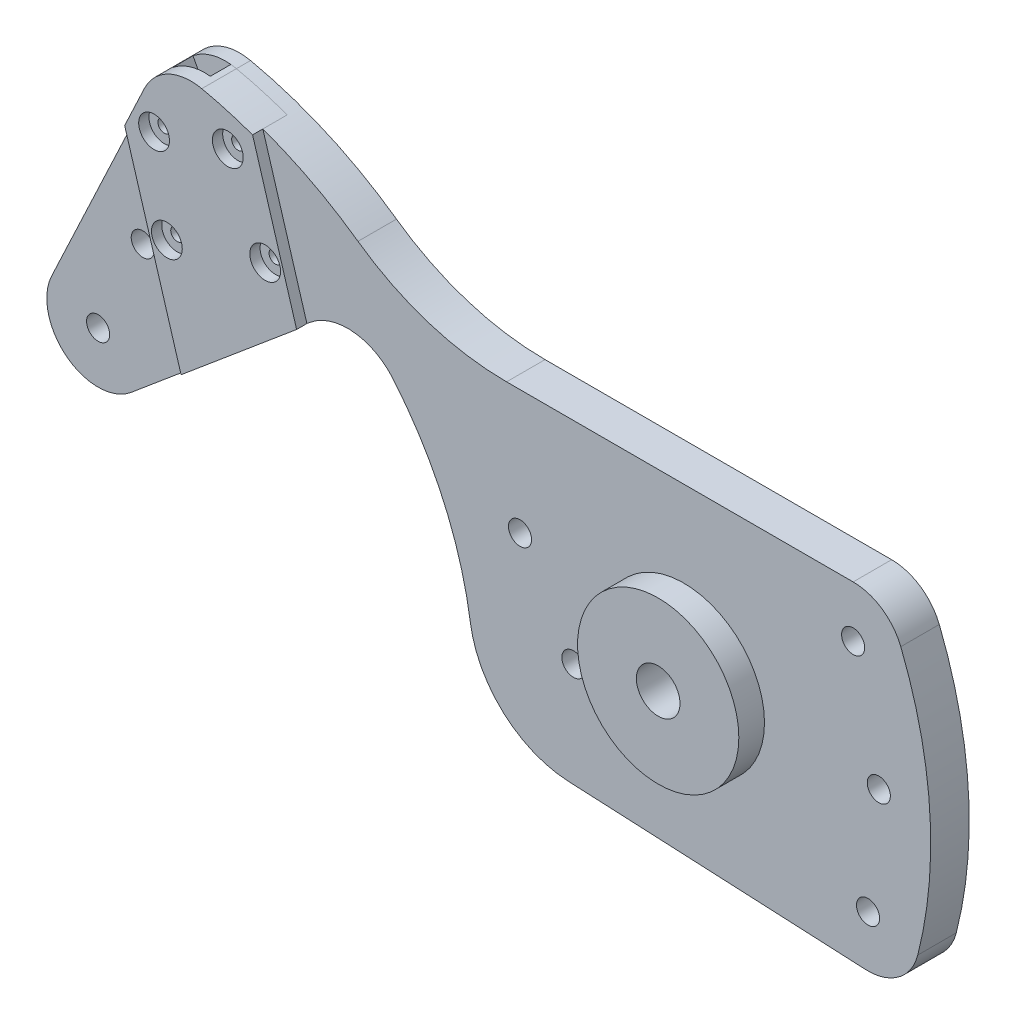
SolidWorks part; units mm, degrees
ref_plane "Front Plane" through (0, 0, 0) normal (0, 0, 1) x (1, 0, 0)
ref_plane "Top Plane" through (0, 0, 0) normal (0, 1, 0) x (1, 0, 0)
ref_plane "Right Plane" through (0, 0, 0) normal (1, 0, 0) x (0, 0, -1)
sketch "Sketch1" plane through (0, 0, 0) normal (0, 0, 1) x (1, 0, 0)
  line L1 (-4.25, -4.25) -> (4.25, -4.25) construction
  line L2 (-4.25, -4.25) -> (-4.25, 4.25) construction
  line L3 (-4.25, 4.25) -> (4.25, 4.25) construction
  line L4 (4.25, -4.25) -> (4.25, 4.25) construction
  line L5 (-4.25, -4.25) -> (4.25, 4.25) construction
  line L6 (-4.25, 4.25) -> (4.25, -4.25) construction
  line L7 (35.3984, -31.7883) -> (-22.5002, -28.984)
  line L9 (-114.4671, 24.4556) -> (-123.1671, 5.9556)
  line L10 (-107.6899, -5.9604) -> (-72.8648, 23.2613)
  line L11 (-114.4671, 24.4556) -> (-103.0859, 48.6569)
  line L16 (-65.4725, 14.4515) -> (-108.3178, -21.5) construction
  line L17 (50.9822, -33.5) -> (-177.2181, -33.5) construction
  line L20 (-34.5382, 32.4) -> (32.9822, 32.4)
  circle A0 centre (0, 0) radius 4.25
  circle A1 centre (-31.9178, 8.2) radius 2.25
  circle A2 centre (-21.5178, -8.7) radius 2.25
  circle A3 centre (32.9822, 22.4) radius 2.25
  circle A4 centre (37.9822, -0.1) radius 2.25
  circle A5 centre (35.8822, -21.8) radius 2.25
  circle A6 centre (35.8822, -21.8) radius 2.25 construction
  circle A7 centre (37.9822, -0.1) radius 2.25 construction
  circle A8 centre (32.9822, 22.4) radius 2.25 construction
  circle A9 centre (-31.9178, 8.2) radius 2.25 construction
  circle A10 centre (-21.5178, -8.7) radius 2.25 construction
  arc A12 (-41.6083, -11.6627) -> (-22.5002, -28.984) centre (-21.5178, -8.7) ccw
  arc A13 (32.5913, -31.6523) -> (28.0429, 32.4) centre (-33.3577, -4.1478) ccw construction
  arc A14 (45.5723, -24.2704) -> (42.2664, 26.1153) centre (-33.3577, -4.1478) ccw
  arc A15 (35.3984, -31.7883) -> (45.5723, -24.2704) centre (35.8822, -21.8) ccw
  arc A16 (42.2664, 26.1153) -> (32.9822, 32.4) centre (32.9822, 22.4) ccw
  circle A17 centre (-105.4178, 20.2) radius 2.25
  circle A18 centre (-33.3577, -4.1478) radius 81.4546 construction
  circle A19 centre (-114.1178, 1.7) radius 2.25
  circle A21 centre (-105.4178, 20.2) radius 2.25 construction
  circle A22 centre (-114.1178, 1.7) radius 2.25 construction
  circle A23 centre (-105.4178, 20.2) radius 10 construction
  arc A24 (-123.1671, 5.9556) -> (-107.6899, -5.9604) centre (-114.1178, 1.7) ccw
  arc A27 (-91.9187, 54.1744) -> (-103.0859, 48.6569) centre (-94.0366, 44.4013) ccw
  circle A31 centre (-33.3577, -4.1478) radius 71.4546 construction
  arc A32 (-41.6083, -11.6627) -> (-56.6627, 21.8438) centre (-108.3178, -21.5) ccw
  arc A33 (-31.0568, -26.628) -> (-91.9187, 54.1744) centre (-108.3178, -21.5) ccw
  arc A34 (-63.487, 41.6328) -> (-34.5382, 32.4) centre (-34.5382, 82.4) ccw
  arc A35 (-56.6627, 21.8438) -> (-72.8648, 23.2613) centre (-65.4725, 14.4515) ccw
  circle A36 centre (-65.4725, 14.4515) radius 10.5004 construction
  circle A37 centre (-108.3178, -21.5) radius 67.4309 construction
  circle A38 centre (-108.3178, -21.5) radius 77.4309 construction
  circle A39 centre (-108.3178, -21.5) radius 10.5004 construction
  circle A40 centre (-108.3178, -21.5) radius 11.5004 construction
  circle A41 centre (0, 0) radius 33 construction
  point P35 (50.3427, -4.5217)
  point P37 (37.1696, 16.7103)
  point P54 (-36.0565, -0.0269)
  point P75 (-40.8381, -1.4887)
  dimension "D1" = 8.5
  dimension "D3" = 10
  dimension "D5" = 50
  dimension "D7" = 40
  dimension "D4" = 10
  dimension "D2" = 10
  dimension "D8" = 1
extrude "Boss-Extrude1" add sketch "Sketch1" along normal mid plane 9.5 contours A0 L4 L3 | A0 L1 L4 | A0 L2 L1 | A0 L3 L2 | A35 A32 A12 A33 A27 L11 L9 A24 L10 A17 A19
sketch "Sketch2" plane through (0, 0, 0) normal (0, 0, 1) x (1, 0, 0)
  line L0 (-94.0366, 44.4013) -> (-96.9145, 53.9782) construction
  line L1 (-78.2271, 18.7618) -> (-72.8648, 23.2613)
  line L2 (-94.0366, 44.4013) -> (-84.6999, 13.3304) construction
  line L3 (-92.0846, 44.9879) -> (-78.2271, 18.7618)
  line L4 (-95.0124, 54.3536) -> (-94.0366, 44.4013) construction
  line L5 (-94.0366, 44.4013) -> (-90.5122, 8.4534) construction
  line L6 (-98.7084, 53.2429) -> (-94.0366, 44.4013) construction
  line L7 (-94.0366, 44.4013) -> (-79.7943, 17.4467) construction
  line L8 (-100.3823, 52.1299) -> (-95.9887, 43.8147)
  line L9 (-93.0022, 54.3476) -> (-92.0846, 44.9879)
  line L12 (-92.369, 6.8953) -> (-78.2271, 18.7618)
  line L13 (-107.6899, -5.9604) -> (-72.8648, 23.2613) construction
  line L14 (-101.3327, 53.9285) -> (-91.0539, 34.4751) construction
  line L15 (-93.2007, 56.3721) -> (-91.0539, 34.4751) construction
  line L16 (-95.9887, 43.8147) -> (-92.369, 6.8953)
  line L18 (-97.0194, 54.3274) -> (-78.2271, 18.7618) construction
  line L19 (-97.0194, 54.3274) -> (-92.369, 6.8953) construction
  line L20 (-92.369, 6.8953) -> (-107.6899, -5.9604)
  line L22 (-94.0366, 44.4013) -> (-90.3786, 7.0905) construction
  line L23 (-94.0366, 44.4013) -> (-79.9955, 17.8274) construction
  arc A0 (-93.0022, 54.3476) -> (-100.3823, 52.1299) centre (-94.0366, 44.4013) ccw
  arc A1 (-95.0124, 54.3536) -> (-98.7084, 53.2429) centre (-94.0366, 44.4013) ccw construction
  arc A2 (-93.2007, 56.3721) -> (-101.3327, 53.9285) centre (-94.0366, 44.4013) ccw construction
  arc A3 (-91.9187, 54.1744) -> (-103.0859, 48.6569) centre (-94.0366, 44.4013) ccw construction
  point P33 (-96.9145, 53.9782)
  dimension "D3" = 7
  dimension "D4" = 20
  dimension "D1" = 2
  dimension "D2" = 2
extrude "Cut-Extrude1" cut sketch "Sketch2" against normal mid plane 4
ref_plane "Plane1" through (-20.0256, 66.6414, 0) normal (-0.2878, 0.9577, 0) x (0.9577, 0.2878, 0)
sketch "Sketch4" plane through (0, 0, 4.75) normal (0, 0, 1) x (1, 0, 0)
  line L10 (-101.2193, 42.2429) -> (-86.8539, 46.5597) construction
  line L11 (-17.9186, 67.2745) -> (-22.1325, 66.0083) construction
  line L12 (-98.7212, 25.2426) -> (-79.5673, 30.9983) construction
  line L13 (-94.0366, 44.4013) -> (-89.1443, 28.1205) construction
  line L15 (-92.0846, 44.9879) -> (-93.0022, 54.3476)
  line L16 (-78.2271, 18.7618) -> (-92.0846, 44.9879)
  line L17 (-92.369, 6.8953) -> (-78.2271, 18.7618)
  line L18 (-95.9887, 43.8147) -> (-92.369, 6.8953)
  line L19 (-100.3823, 52.1299) -> (-95.9887, 43.8147)
  line L20 (-92.0846, 44.9879) -> (-93.0022, 54.3476) construction
  line L21 (-78.2271, 18.7618) -> (-92.0846, 44.9879) construction
  line L22 (-92.369, 6.8953) -> (-78.2271, 18.7618) construction
  line L23 (-95.9887, 43.8147) -> (-92.369, 6.8953) construction
  line L24 (-100.3823, 52.1299) -> (-95.9887, 43.8147) construction
  circle A0 centre (-98.7212, 25.2426) radius 1.25
  circle A1 centre (-101.2193, 42.2429) radius 1.25
  circle A2 centre (-86.8539, 46.5597) radius 1.25
  circle A3 centre (-79.5673, 30.9983) radius 1.25
  arc A7 (-93.0022, 54.3476) -> (-100.3823, 52.1299) centre (-94.0366, 44.4013) ccw
  arc A8 (-93.0022, 54.3476) -> (-100.3823, 52.1299) centre (-94.0366, 44.4013) ccw construction
  point P13 (-94.0366, 44.4013)
  dimension "D3" = 2.5
  dimension "D2" = 17
  dimension "D4" = 15
  dimension "D5" = 20
  dimension "D1" = 0
extrude "Cut-Extrude2" cut sketch "Sketch4" against normal through all
sketch "Sketch5" plane through (0, 0, 4.75) normal (0, 0, 1) x (1, 0, 0)
  circle A49 centre (-101.2193, 42.2429) radius 3
  circle A50 centre (-86.8539, 46.5597) radius 3
  circle A51 centre (-79.5673, 30.9983) radius 3
  circle A52 centre (-98.7212, 25.2426) radius 3
  dimension "D1" = 6
extrude "Cut-Extrude3" cut sketch "Sketch5" against normal blind 2
sketch "Sketch3" plane through (-20.0256, 66.6414, 0) normal (-0.2878, 0.9577, 0) x (0.9577, 0.2878, 0)
  line L0 (-90.7804, 2) -> (-63.7804, 2)
  line L1 (-63.7804, 2) -> (-63.7804, -4.75)
  line L2 (-72.4396, -4.75) -> (-48.8199, -4.75) construction
  line L3 (-90.7804, 2) -> (-90.7804, -4.75)
  line L4 (-116.2426, -4.75) -> (-84.7222, -4.75) construction
  line L11 (-79.3187, 2) -> (-75.2421, 2) construction
  point P3 (-77.2804, 2)
  point P11 (-77.2804, 2)
  dimension "D1" = 27
split "Split3" trim tools "Sketch3" bodies to split 111 resulting bodies 112 113
sketch "Sketch6" plane through (0, 0, 4.75) normal (0, 0, 1) x (1, 0, 0)
  line L6 (-95.9577, 3.8841) -> (-106.9455, 40.4497)
  line L7 (-106.9455, 40.4497) -> (-123.1671, 5.9556)
  line L8 (-107.6899, -5.9604) -> (-95.9577, 3.8841)
  line L9 (-95.9577, 3.8841) -> (-106.9455, 40.4497)
  line L10 (-106.9455, 40.4497) -> (-123.1671, 5.9556)
  line L11 (-107.6899, -5.9604) -> (-95.9577, 3.8841)
  line L17 (-82.0221, 51.3292) -> (-73.4422, 22.7768)
  line L18 (-73.4422, 22.7768) -> (-72.8648, 23.2613)
  line L19 (-22.5002, -28.984) -> (35.3984, -31.7883)
  line L20 (32.9822, 32.4) -> (-34.5382, 32.4)
  line L21 (-82.0221, 51.3292) -> (-73.4422, 22.7768)
  line L22 (-73.4422, 22.7768) -> (-72.8648, 23.2613)
  line L23 (-22.5002, -28.984) -> (35.3984, -31.7883)
  line L24 (32.9822, 32.4) -> (-34.5382, 32.4)
  circle A0 centre (0, 0) radius 15.71
  circle A1 centre (-21.5178, -8.7) radius 7.5 construction
  arc A2 (-123.1671, 5.9556) -> (-107.6899, -5.9604) centre (-114.1178, 1.7) ccw
  arc A3 (-123.1671, 5.9556) -> (-107.6899, -5.9604) centre (-114.1178, 1.7) ccw
  arc A19 (-56.6627, 21.8438) -> (-72.8648, 23.2613) centre (-65.4725, 14.4515) ccw
  arc A20 (-41.6083, -11.6627) -> (-56.6627, 21.8438) centre (-108.3178, -21.5) ccw
  arc A21 (-41.6083, -11.6627) -> (-22.5002, -28.984) centre (-21.5178, -8.7) ccw
  arc A22 (35.3984, -31.7883) -> (45.5723, -24.2704) centre (35.8822, -21.8) ccw
  arc A23 (45.5723, -24.2704) -> (42.2664, 26.1153) centre (-33.3577, -4.1478) ccw
  arc A24 (42.2664, 26.1153) -> (32.9822, 32.4) centre (32.9822, 22.4) ccw
  arc A25 (-63.487, 41.6328) -> (-34.5382, 32.4) centre (-34.5382, 82.4) ccw
  arc A26 (-63.487, 41.6328) -> (-82.0221, 51.3292) centre (-108.3178, -21.5) ccw
  arc A27 (-56.6627, 21.8438) -> (-72.8648, 23.2613) centre (-65.4725, 14.4515) ccw
  arc A28 (-41.6083, -11.6627) -> (-56.6627, 21.8438) centre (-108.3178, -21.5) ccw
  arc A29 (-41.6083, -11.6627) -> (-22.5002, -28.984) centre (-21.5178, -8.7) ccw
  arc A30 (35.3984, -31.7883) -> (45.5723, -24.2704) centre (35.8822, -21.8) ccw
  arc A31 (45.5723, -24.2704) -> (42.2664, 26.1153) centre (-33.3577, -4.1478) ccw
  arc A32 (42.2664, 26.1153) -> (32.9822, 32.4) centre (32.9822, 22.4) ccw
  arc A33 (-63.487, 41.6328) -> (-34.5382, 32.4) centre (-34.5382, 82.4) ccw
  arc A34 (-63.487, 41.6328) -> (-82.0221, 51.3292) centre (-108.3178, -21.5) ccw
  dimension "D3" = 15
  dimension "D1" = 0
  dimension "D2" = 0
extrude "Cut-Extrude4" cut sketch "Sketch6" against normal blind 2
sketch "Sketch7" plane through (0, 0, 4.75) normal (0, 0, 1) x (1, 0, 0)
  circle A2 centre (0, 0) radius 15.71
  circle A3 centre (0, 0) radius 15.71
  circle A5 centre (0, 0) radius 4.25
  circle A6 centre (0, 0) radius 4.25
  dimension "D1" = 0
  dimension "D2" = 0
extrude "Boss-Extrude2" add sketch "Sketch7" along normal blind 3
